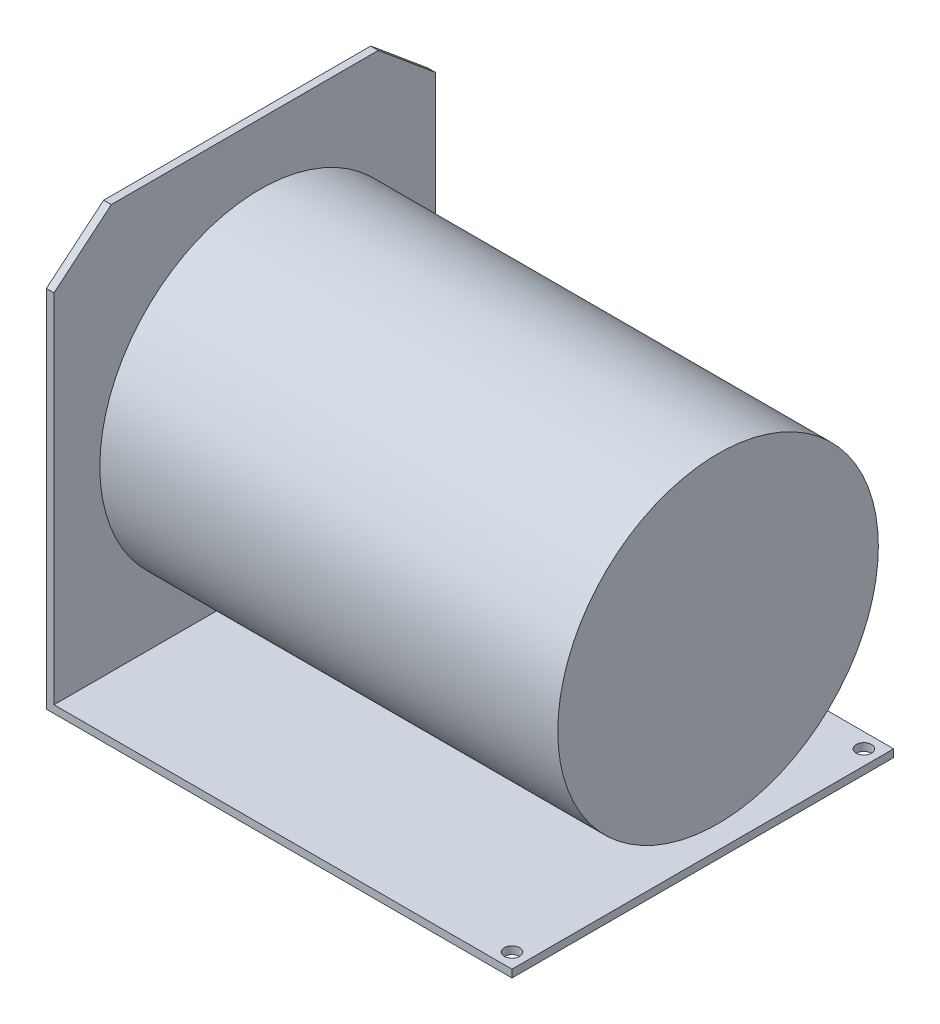
SolidWorks part; units mm, degrees
ref_plane "Plan de face" through (0, 0, 0) normal (0, 0, 1) x (1, 0, 0)
ref_plane "Plan de dessus" through (0, 0, 0) normal (0, 1, 0) x (1, 0, 0)
ref_plane "Plan de droite" through (0, 0, 0) normal (1, 0, 0) x (0, 0, -1)
sketch "Esquisse1" plane through (0, 0, 0) normal (1, 0, 0) x (0, 0, -1)
  circle A0 centre (0, 0) radius 10.5
  dimension "D1" = 21
extrude "Boss.-Extru.1" add sketch "Esquisse1" along normal blind 30
sketch "Esquisse2" plane through (0, 0, 0) normal (-1, 0, 0) x (0, 0, 1)
  circle A0 centre (0, 0) radius 6
  dimension "D1" = 12
extrude "Boss.-Extru.2" add sketch "Esquisse2" along normal blind 1
ref_plane "Plan1" through (-1, 0, 0) normal (-1, 0, 0) x (0, 0, 1)
sketch "Esquisse3" plane through (-1, 0, 0) normal (-1, 0, 0) x (0, 0, 1)
  line L1 (-12.5, 13.5) -> (12.5, 13.5)
  line L2 (-12.5, 13.5) -> (-12.5, -13.5)
  line L3 (-12.5, -13.5) -> (12.5, -13.5)
  line L4 (12.5, 13.5) -> (12.5, -13.5)
  line L5 (-12.5, 13.5) -> (12.5, -13.5) construction
  line L6 (-12.5, -13.5) -> (12.5, 13.5) construction
  point P0 (0, 0)
  dimension "D1" = 27
  dimension "D2" = 25
extrude "Boss.-Extru.3" add sketch "Esquisse3" along normal blind 0.5 separate body
sketch "Esquisse4" plane through (-1, 0, 0) normal (1, 0, 0) x (0, 0, -1)
  line L0 (12.5, 13.5) -> (12.5, -13.5) construction
  line L1 (-12.5, -13.5) -> (12.5, -13.5)
  line L2 (-12.5, -13.5) -> (-12.5, -13)
  line L3 (-12.5, -13) -> (12.5, -13)
  line L4 (12.5, -13.5) -> (12.5, -13)
  dimension "D1" = 0.5
extrude "Boss.-Extru.4" add sketch "Esquisse4" along normal blind 30
sketch "Esquisse5" plane through (0, -13.5, 0) normal (0, -1, 0) x (1, 0, 0)
  circle A0 centre (28.028, 11.526) radius 0.5
  dimension "D1" = 1
extrude "Enlèv. mat.-Extru.1" cut sketch "Esquisse5" against normal blind 30
mirror "Symétrie1" about plane through (0, 0, 0) normal (0, 0, 1) of "Enlèv. mat.-Extru.1"
sketch "Esquisse6" plane through (-1.5, 0, 0) normal (-1, 0, 0) x (0, 0, 1)
  line L0 (8.746, 13.5) -> (12.5, 10.3724)
  line L1 (12.5, 13.5) -> (-12.5, 13.5) construction
  line L2 (12.5, -13.5) -> (12.5, 13.5) construction
  line L3 (12.5, 10.3724) -> (12.5, 13.5)
  line L4 (12.5, 13.5) -> (8.746, 13.5)
extrude "Enlèv. mat.-Extru.2" cut sketch "Esquisse6" against normal blind 30
mirror "Symétrie2" about plane through (0, 0, 0) normal (0, 0, 1) of "Enlèv. mat.-Extru.2"
sketch "Esquisse7" plane through (-1.5, 0, 0) normal (-1, 0, 0) x (0, 0, 1)
  circle A0 centre (0, 0) radius 1
  dimension "D1" = 2
extrude "Boss.-Extru.5" add sketch "Esquisse7" along normal blind 8
